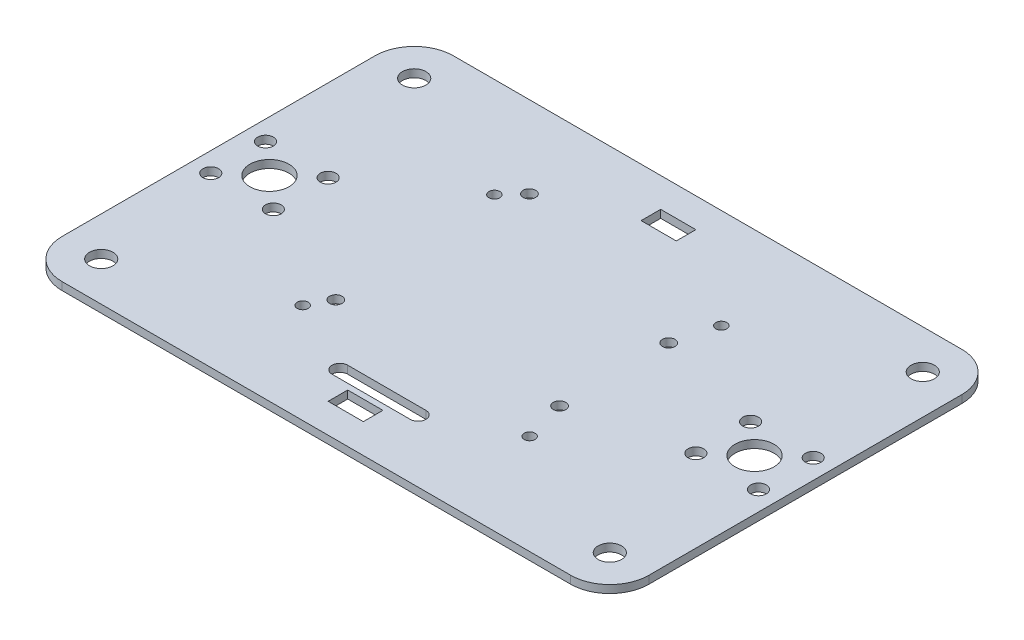
SolidWorks part; units mm, degrees
ref_plane "Front Plane" through (0, 0, 0) normal (0, 0, 1) x (1, 0, 0)
ref_plane "Top Plane" through (0, 0, 0) normal (0, 1, 0) x (1, 0, 0)
ref_plane "Right Plane" through (0, 0, 0) normal (1, 0, 0) x (0, 0, -1)
sketch "Sketch1" plane through (0, 0, 0) normal (0, 1, 0) x (1, 0, 0)
  line L0 (26.1093, 13.95) -> (26.1093, -13.95) construction
  line L1 (-65, -50) -> (65, -50)
  line L2 (-75, -40) -> (-75, 40)
  line L3 (-65, 50) -> (65, 50)
  line L4 (75, -40) -> (75, 40)
  line L5 (-75, -50) -> (75, 50) construction
  line L6 (-75, 50) -> (75, -50) construction
  line L7 (-29, -24.5) -> (29, -24.5) construction
  line L8 (-29, -24.5) -> (-29, 24.5) construction
  line L9 (-29, 24.5) -> (29, 24.5) construction
  line L10 (29, -24.5) -> (29, 24.5) construction
  line L11 (-29, -24.5) -> (29, 24.5) construction
  line L12 (-29, 24.5) -> (29, -24.5) construction
  line L13 (26.1093, -13.95) -> (26.1093, 0) construction
  line L14 (26.1093, 0) -> (-26.1093, 0) construction
  line L15 (-25.9907, -19.05) -> (-26.2907, 29.15) construction
  line L16 (0, 0) -> (0, 50) construction
  line L21 (70, 7) -> (54, -7) construction
  line L22 (-4.5, 42.5) -> (4.5, 42.5)
  line L23 (-4.5, 42.5) -> (-4.5, 37.5)
  line L24 (-4.5, 37.5) -> (4.5, 37.5)
  line L25 (4.5, 42.5) -> (4.5, 37.5)
  line L26 (-4.5, 42.5) -> (4.5, 37.5) construction
  line L27 (-4.5, 37.5) -> (4.5, 42.5) construction
  line L28 (-70, -7) -> (-54, -7) construction
  line L29 (-70, -7) -> (-70, 7) construction
  line L30 (-70, 7) -> (-54, 7) construction
  line L31 (-54, -7) -> (-54, 7) construction
  line L32 (-70, -7) -> (-54, 7) construction
  line L33 (-70, 7) -> (-54, -7) construction
  line L34 (70, -7) -> (54, 7) construction
  line L35 (70, 7) -> (54, 7) construction
  line L36 (54, -7) -> (54, 7) construction
  line L37 (70, -7) -> (54, -7) construction
  line L38 (70, -7) -> (70, 7) construction
  line L39 (-4.5, -37.5) -> (4.5, -42.5) construction
  line L40 (-4.5, -42.5) -> (4.5, -37.5) construction
  line L41 (-4.5, -37.5) -> (4.5, -37.5)
  line L42 (4.5, -42.5) -> (4.5, -37.5)
  line L43 (-4.5, -42.5) -> (-4.5, -37.5)
  line L44 (-4.5, -42.5) -> (4.5, -42.5)
  line L45 (-10, -34) -> (10, -34) construction
  line L46 (-10, -32) -> (10, -32)
  line L47 (-10, -36) -> (10, -36)
  arc A0 (-65, -50) -> (-75, -40) centre (-65, -40) cw
  arc A1 (65, -50) -> (75, -40) centre (65, -40) ccw
  arc A2 (65, 50) -> (75, 40) centre (65, 40) cw
  arc A3 (-75, 40) -> (-65, 50) centre (-65, 40) cw
  circle A4 centre (-29, 24.5) radius 1.4
  circle A6 centre (29, 24.5) radius 1.4
  circle A7 centre (-29, -24.5) radius 1.4
  circle A8 centre (29, -24.5) radius 1.4
  circle A9 centre (-24.6907, 29.15) radius 1.6
  circle A10 centre (-25.9907, -19.05) radius 1.6
  circle A11 centre (26.1093, 13.95) radius 1.6
  circle A12 centre (26.1093, -13.95) radius 1.6
  circle A13 centre (-65, 40) radius 3
  circle A14 centre (65, 40) radius 3
  circle A15 centre (65, -40) radius 3
  circle A16 centre (-65, -40) radius 3
  circle A17 centre (-62, 0) radius 5
  circle A20 centre (-70, 7) radius 2
  circle A21 centre (-54, 7) radius 2
  circle A22 centre (-54, -7) radius 2
  circle A23 centre (-70, -7) radius 2
  circle A24 centre (70, -7) radius 2
  circle A25 centre (70, 7) radius 2
  circle A26 centre (54, -7) radius 2
  circle A27 centre (62, 0) radius 5
  circle A28 centre (54, 7) radius 2
  arc A29 (-10, -32) -> (-10, -36) centre (-10, -34) ccw
  arc A30 (10, -36) -> (10, -32) centre (10, -34) ccw
  point P0 (0, 0)
  point P18 (0, 0)
  point P37 (0, 0)
  point P44 (0, 40)
  point P58 (0, -34)
  point P67 (0, 0)
  point P68 (0, -40)
  point P69 (0, 0)
  point P80 (-4.5, 40)
  point P85 (-4.5, -40)
  point P86 (0, -33.1509)
  dimension "D3" = 10
  dimension "D6" = 2.8
  dimension "D8" = 3.2
  dimension "D13" = 6
  dimension "D14" = 10
  dimension "D19" = 4
  dimension "D1" = 150
  dimension "D2" = 100
  dimension "D4" = 58
  dimension "D5" = 49
  dimension "D7" = 1.3
  dimension "D9" = 15.2
  dimension "D10" = 27.9
  dimension "D11" = 5.1
  dimension "D12" = 50.8
  dimension "D15" = 14
  dimension "D16" = 9
  dimension "D17" = 5
  dimension "D18" = 16
  dimension "D20" = 13
  dimension "D21" = 20
  dimension "D22" = 4
  dimension "D23" = 6
extrude "Boss-Extrude1" add sketch "Sketch1" along normal mid plane 2 contours A3 L2 A0 L1 A1 L4 A2 L3 L22 L25 L24 L23 A4 A6 A7 A8 A9 A10 A11 A12 A13 A14 A15 A16 A17 A20
